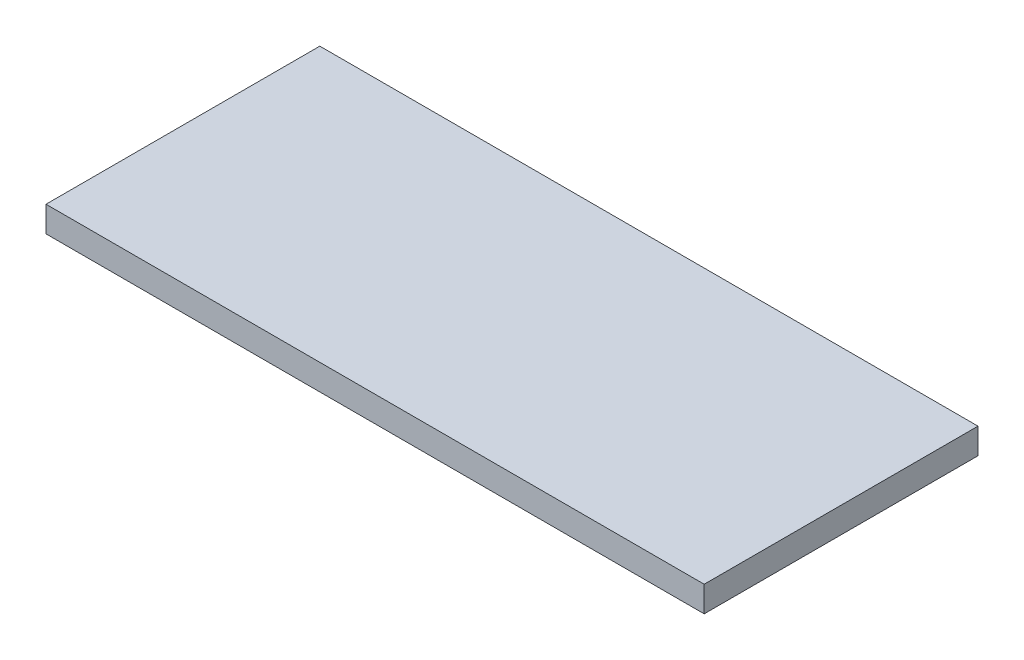
SolidWorks part; units mm, degrees
material "Balsa"
ref_plane "Front Plane" through (0, 0, 0) normal (0, 0, 1) x (1, 0, 0)
ref_plane "Top Plane" through (0, 0, 0) normal (0, 1, 0) x (1, 0, 0)
ref_plane "Right Plane" through (0, 0, 0) normal (1, 0, 0) x (0, 0, -1)
sketch "Sketch1" plane through (0, 0, 0) normal (0, 1, 0) x (1, 0, 0)
  line L0 (0, 0) -> (0, 50.8)
  line L1 (0, 50.8) -> (122.1105, 50.8)
  line L2 (122.1105, 50.8) -> (122.1105, 0)
  line L3 (122.1105, 0) -> (0, 0)
  dimension "D1" = 50.8
  dimension "D2" = 122.1105
extrude "Boss-Extrude1" add sketch "Sketch1" along normal blind 4.7625
